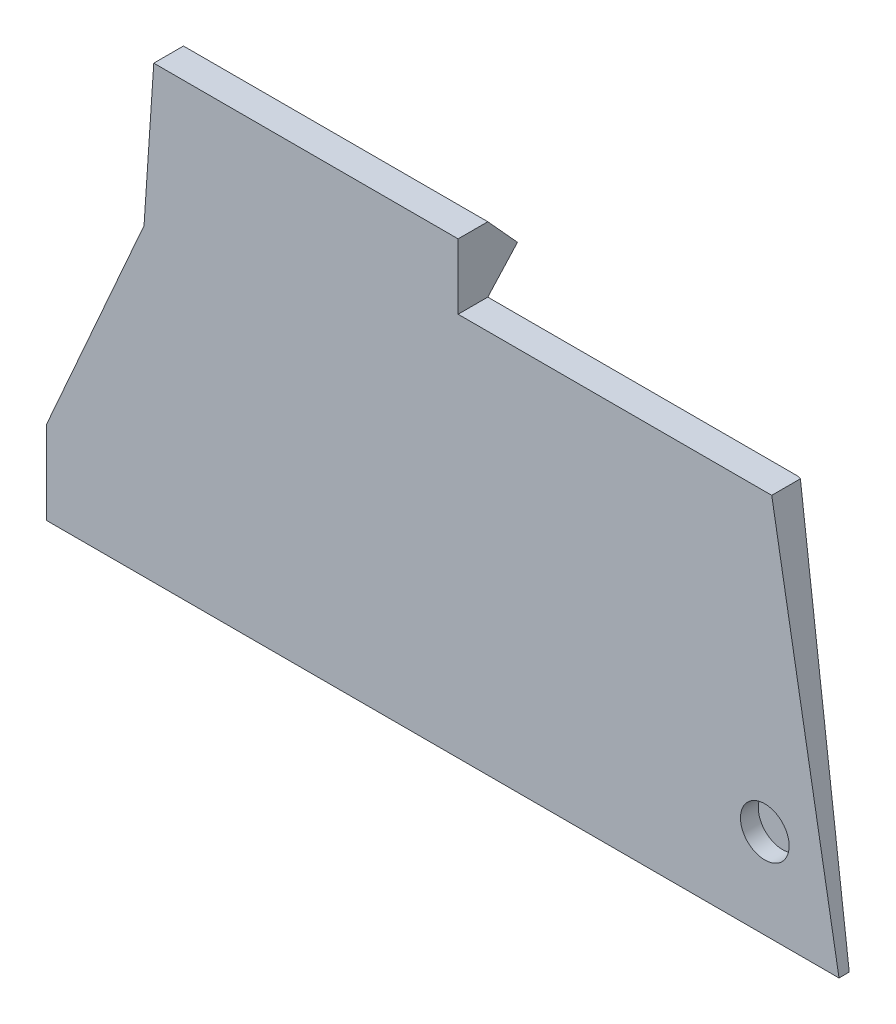
SolidWorks part; units mm, degrees
ref_plane "Plan de face" through (0, 0, 0) normal (0, 0, 1) x (1, 0, 0)
ref_plane "Plan de dessus" through (0, 0, 0) normal (0, 1, 0) x (1, 0, 0)
ref_plane "Plan de droite" through (0, 0, 0) normal (1, 0, 0) x (0, 0, -1)
sketch "Esquisse1" plane through (0, 18.2754, 0) normal (0, 1, 0) x (1, 0, 0)
  line L0 (59.972, -14.9403) -> (23.3933, -4.9403)
  line L1 (23.3933, -4.9403) -> (-35.4996, -4.9403)
  line L2 (-35.4996, -4.9403) -> (-79.8173, -9.9403)
  line L3 (-79.8173, -9.9403) -> (-79.8173, -14.9403)
  line L4 (-79.8173, -14.9403) -> (59.972, -14.9403)
  line L5 (59.848, -14.9064) -> (41.6827, -9.9403) construction
  line L6 (41.6827, -9.9403) -> (-79.8173, -9.9403) construction
  dimension "D1" = 5
extrude "Boss.-Extru.1" add sketch "Esquisse1" along normal up to surface (75.755 mm away)
sketch "Esquisse2" plane through (0, 0, 14.9403) normal (0, 0, 1) x (1, 0, 0)
  line L0 (-79.8173, 32.3782) -> (-63.4282, 69.4892)
  line L1 (-63.4282, 69.4892) -> (-61.7863, 94.0304)
  line L2 (-61.7863, 94.0304) -> (-79.8173, 94.0304)
  line L3 (-79.8173, 94.0304) -> (-79.8173, 32.3782)
  line L4 (-10.5154, 94.0304) -> (-10.5154, 83.0304)
  line L5 (-10.5154, 83.0304) -> (42.319, 83.0304)
  line L6 (42.319, 83.0304) -> (59.972, -17.8291)
  line L7 (59.972, 94.0304) -> (59.972, 18.2754) construction
  line L8 (59.972, -17.8291) -> (59.972, 94.0304)
  line L9 (59.972, 94.0304) -> (-10.5154, 94.0304)
  line L11 (42.319, 83.0304) -> (51.0155, 33.343) construction
extrude "Enlèv. mat.-Extru.1" cut sketch "Esquisse2" against normal through all
sketch "Esquisse3" plane through (-79.8173, 0, 0) normal (-1, 0, 0) x (0, 0, 1)
  line L0 (9.9403, 18.2754) -> (4.9403, 18.2754)
  line L2 (4.9403, 94.0304) -> (4.9403, 18.2754) construction
  line L3 (4.9403, 26.2754) -> (9.9403, 18.2754)
  line L4 (9.9403, 18.2754) -> (9.9403, 94.0304) construction
  line L5 (7.9061, 94.0304) -> (14.9403, 94.0304) construction
  line L6 (4.9403, 26.2754) -> (9.9403, 34.3832)
  line L7 (9.9403, 34.3832) -> (4.9403, 42.4911)
  line L8 (9.9403, 94.0304) -> (4.9403, 88.5304)
  line L9 (9.9403, 66.8147) -> (4.9403, 58.7068)
  line L10 (4.9403, 94.0304) -> (4.9403, 18.2754) construction
  line L11 (4.9403, 88.5304) -> (9.9403, 83.0304)
  line L12 (9.9403, 94.0304) -> (4.9403, 94.0304)
  line L13 (4.9403, 18.2754) -> (4.9403, 94.0304)
  line L14 (4.9403, 94.0304) -> (4.9403, 26.2754)
  line L15 (4.9403, 26.2754) -> (4.9403, 94.0304)
  line L16 (4.9403, 94.0304) -> (4.9403, 26.2754)
  line L20 (4.9403, 58.7068) -> (9.9403, 50.5989)
  line L21 (9.9403, 50.5989) -> (4.9403, 42.4911)
  line L23 (9.9403, 83.0304) -> (4.9403, 74.9225)
  line L24 (4.9403, 74.9225) -> (9.9403, 66.8147)
  line L26 (107.1622, 83.0304) -> (105.4708, 83.0304) construction
  point P7 (9.9403, 66.8147)
  dimension "D1" = 8
extrude "Enlèv. mat.-Extru.2" cut sketch "Esquisse3" against normal through all
sketch "Esquisse4" plane through (0, 83.0304, 0) normal (0, 1, 0) x (1, 0, 0)
  line L0 (-79.8173, -9.9403) -> (41.6827, -9.9403) construction
  line L1 (-79.8173, -9.9403) -> (-78.9981, -9.8479) construction
  line L2 (41.6827, -9.9403) -> (42.319, -10.1143) construction
  line L4 (-79.8173, -14.9403) -> (-63.4282, -14.9403) construction
  line L6 (-61.9348, -7.9228) -> (-44.4948, -4.9403)
  line L7 (-44.4948, -4.9403) -> (-27.5228, -9.9403)
  line L8 (-27.5228, -9.9403) -> (-10.5507, -4.9403)
  line L9 (-10.5507, -4.9403) -> (6.4213, -9.9403)
  line L10 (6.4213, -9.9403) -> (23.3933, -4.9403)
  line L11 (23.3933, -4.9403) -> (-79.8173, -4.9403)
  line L14 (-63.4062, -8.0888) -> (-62.7314, -8.0127) construction
  line L16 (-61.9348, -7.9228) -> (-79.8173, -4.9403)
  dimension "D1" = 5
  dimension "D2" = 5
extrude "Enlèv. mat.-Extru.3" cut sketch "Esquisse4" against normal through all contours L10 L11 L9 | L8 L11 L7 | L16 L6 L11
sketch "Esquisse7" plane through (0, 0, 14.9403) normal (0, 0, -1) x (-1, 0, 0)
  circle A0 centre (-41.1527, 33.343) radius 4.1
  dimension "D1" = 8.2
extrude "Enlèv. mat.-Extru.8" cut sketch "Esquisse7" along normal blind 3
